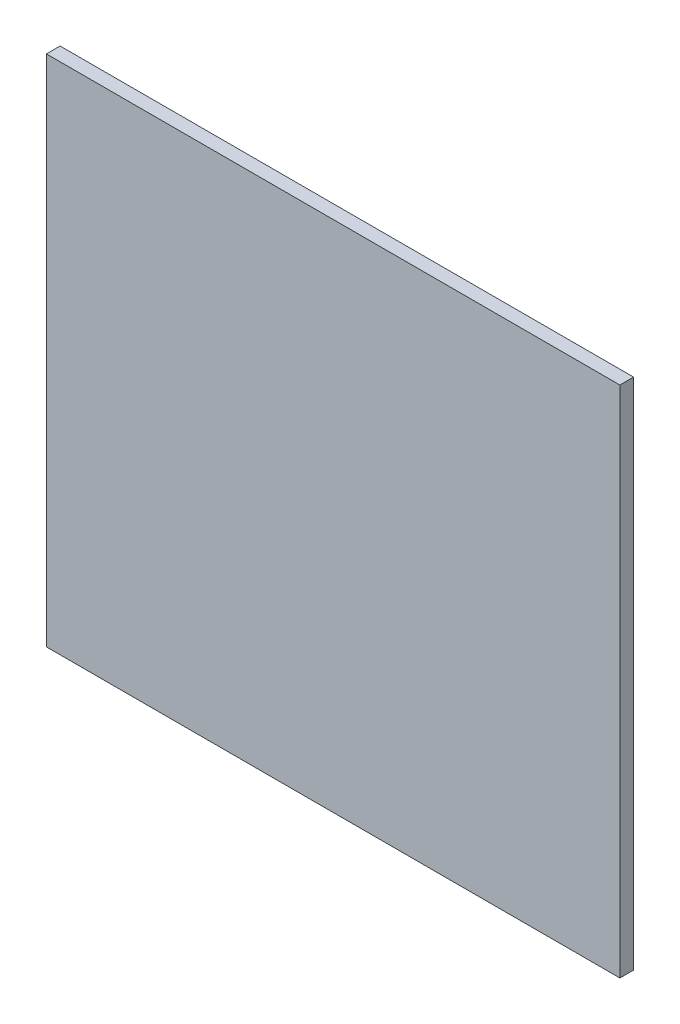
SolidWorks part; units mm, degrees
ref_plane "Front Plane" through (0, 0, 0) normal (0, 0, 1) x (1, 0, 0)
ref_plane "Top Plane" through (0, 0, 0) normal (0, 1, 0) x (1, 0, 0)
ref_plane "Right Plane" through (0, 0, 0) normal (1, 0, 0) x (0, 0, -1)
sketch "Sketch1" plane through (0, 0, 0) normal (0, 0, 1) x (1, 0, 0)
  line L1 (-106.3625, -95.25) -> (106.3625, -95.25)
  line L2 (-106.3625, -95.25) -> (-106.3625, 95.25)
  line L3 (-106.3625, 95.25) -> (106.3625, 95.25)
  line L4 (106.3625, -95.25) -> (106.3625, 95.25)
  line L5 (-106.3625, -95.25) -> (106.3625, 95.25) construction
  line L6 (-106.3625, 95.25) -> (106.3625, -95.25) construction
  point P0 (0, 0)
  dimension "D1" = 212.725
  dimension "D2" = 190.5
extrude "Boss-Extrude1" add sketch "Sketch1" along normal blind 5.08
